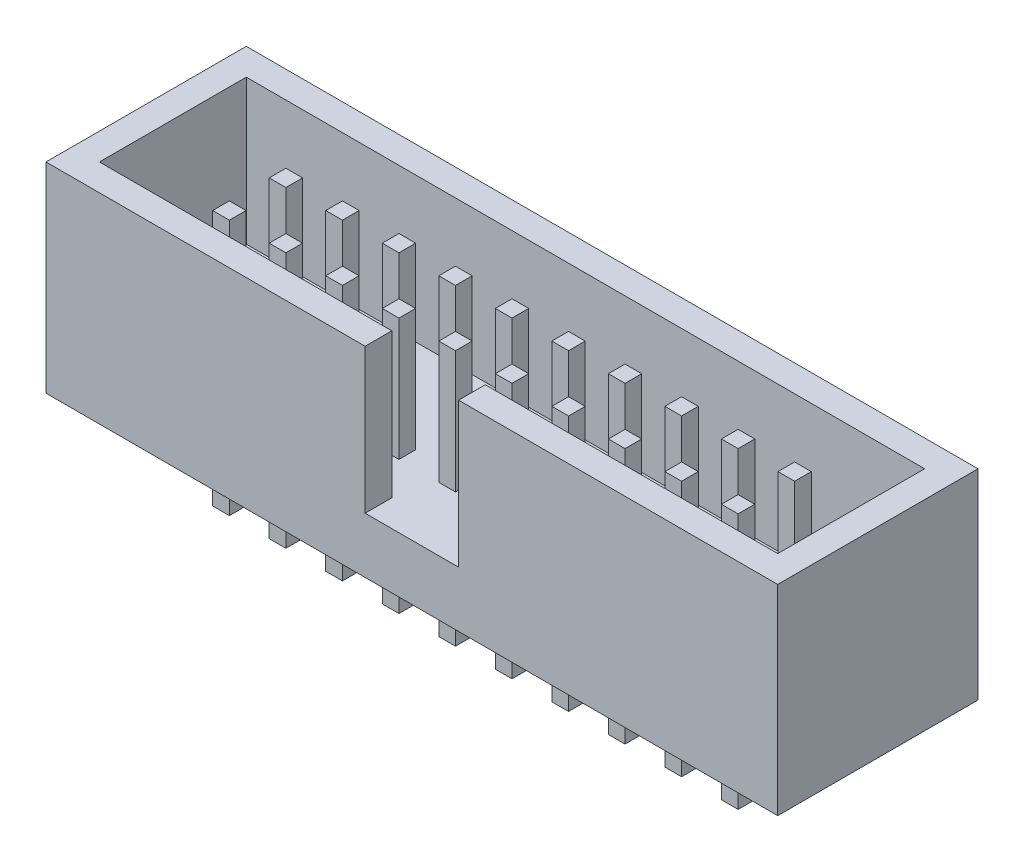
SolidWorks part; units mm, degrees
ref_plane "前视基准面" through (0, 0, 0) normal (0, 0, 1) x (1, 0, 0)
ref_plane "上视基准面" through (0, 0, 0) normal (0, 1, 0) x (1, 0, 0)
ref_plane "右视基准面" through (0, 0, 0) normal (1, 0, 0) x (0, 0, -1)
sketch "草图1" plane through (0, 0, 0) normal (0, 1, 0) x (1, 0, 0)
  line L0 (0, 85.0964) -> (0, -118.2031) construction
  line L1 (-16.44, 4.5) -> (16.44, 4.5)
  line L2 (-16.44, 4.5) -> (-16.44, -4.5)
  line L3 (-16.44, -4.5) -> (16.44, -4.5)
  line L4 (16.44, 4.5) -> (16.44, -4.5)
  line L5 (-200.5452, 0) -> (261.2352, 0) construction
  dimension "D1" = 9
  dimension "D2" = 32.88
extrude "拉伸1" add sketch "草图1" along normal blind 9
sketch "草图2" plane through (0, 9, 0) normal (0, 1, 0) x (-1, 0, 0)
  line L8 (-15.24, 3.3) -> (-15.24, -3.3)
  line L9 (15.24, 3.3) -> (-15.24, 3.3)
  line L10 (15.24, -3.3) -> (15.24, 3.3)
  line L11 (-15.24, -3.3) -> (15.24, -3.3)
  line L12 (-15.24, 3.3) -> (-15.24, -3.3)
  line L13 (15.24, 3.3) -> (-15.24, 3.3)
  line L14 (15.24, -3.3) -> (15.24, 3.3)
  line L15 (-15.24, -3.3) -> (15.24, -3.3)
  dimension "D1" = 1.2
extrude "切除-拉伸1" cut sketch "草图2" against normal blind 6.5
sketch "草图3" plane through (0, 0, 4.5) normal (0, 0, 1) x (1, 0, 0)
  line L0 (-16.44, 9) -> (16.44, 9) construction
  line L1 (-2.1, 9) -> (2.1, 9)
  line L2 (-2.1, 9) -> (-2.1, 2.5)
  line L3 (-2.1, 2.5) -> (2.1, 2.5)
  line L4 (2.1, 9) -> (2.1, 2.5)
  line L5 (-15.24, 2.5) -> (15.24, 2.5) construction
  line L6 (0, 9.4226) -> (0, -4.0288) construction
  dimension "D1" = 4.2
extrude "切除-拉伸2" cut sketch "草图3" against normal blind 6.5
sketch "草图5" plane through (0, 0, 0) normal (0, -1, 0) x (1, 0, 0)
  line L0 (0, 6.0683) -> (0, -6.9786) construction
  line L1 (-14.7999, 0) -> (15.2382, 0) construction
  line L2 (-1.27, 2.5244) -> (-1.27, -0.4442) construction
  line L3 (-1.645, 0.895) -> (-0.895, 0.895)
  line L4 (-1.645, 0.895) -> (-1.645, 1.645)
  line L5 (-1.645, 1.645) -> (-0.895, 1.645)
  line L6 (-0.895, 0.895) -> (-0.895, 1.645)
  line L7 (-2.3518, 1.27) -> (0.5396, 1.27) construction
  line L8 (0.895, 0.895) -> (1.645, 0.895)
  line L9 (0.895, 0.895) -> (0.895, 1.645)
  line L10 (0.895, 1.645) -> (1.645, 1.645)
  line L11 (1.645, 0.895) -> (1.645, 1.645)
  line L12 (3.435, 0.895) -> (4.185, 0.895)
  line L13 (3.435, 0.895) -> (3.435, 1.645)
  line L14 (3.435, 1.645) -> (4.185, 1.645)
  line L15 (4.185, 0.895) -> (4.185, 1.645)
  line L16 (5.975, 0.895) -> (6.725, 0.895)
  line L17 (5.975, 0.895) -> (5.975, 1.645)
  line L18 (5.975, 1.645) -> (6.725, 1.645)
  line L19 (6.725, 0.895) -> (6.725, 1.645)
  line L20 (8.515, 0.895) -> (9.265, 0.895)
  line L21 (8.515, 0.895) -> (8.515, 1.645)
  line L22 (8.515, 1.645) -> (9.265, 1.645)
  line L23 (9.265, 0.895) -> (9.265, 1.645)
  line L24 (11.055, 0.895) -> (11.805, 0.895)
  line L25 (11.055, 0.895) -> (11.055, 1.645)
  line L26 (11.055, 1.645) -> (11.805, 1.645)
  line L27 (11.805, 0.895) -> (11.805, 1.645)
  line L32 (0.895, -1.645) -> (1.645, -1.645)
  line L33 (0.895, -1.645) -> (0.895, -0.895)
  line L34 (0.895, -0.895) -> (1.645, -0.895)
  line L35 (1.645, -1.645) -> (1.645, -0.895)
  line L36 (3.435, -1.645) -> (4.185, -1.645)
  line L37 (3.435, -1.645) -> (3.435, -0.895)
  line L38 (3.435, -0.895) -> (4.185, -0.895)
  line L39 (4.185, -1.645) -> (4.185, -0.895)
  line L40 (5.975, -1.645) -> (6.725, -1.645)
  line L41 (5.975, -1.645) -> (5.975, -0.895)
  line L42 (5.975, -0.895) -> (6.725, -0.895)
  line L43 (6.725, -1.645) -> (6.725, -0.895)
  line L44 (8.515, -1.645) -> (9.265, -1.645)
  line L45 (8.515, -1.645) -> (8.515, -0.895)
  line L46 (8.515, -0.895) -> (9.265, -0.895)
  line L47 (9.265, -1.645) -> (9.265, -0.895)
  line L48 (11.055, -1.645) -> (11.805, -1.645)
  line L49 (11.055, -1.645) -> (11.055, -0.895)
  line L50 (11.055, -0.895) -> (11.805, -0.895)
  line L51 (11.805, -1.645) -> (11.805, -0.895)
  line L54 (-4.185, 0.895) -> (-3.435, 0.895)
  line L55 (-4.185, 0.895) -> (-4.185, 1.645)
  line L56 (-4.185, 1.645) -> (-3.435, 1.645)
  line L57 (-3.435, 0.895) -> (-3.435, 1.645)
  line L58 (-6.725, 0.895) -> (-5.975, 0.895)
  line L59 (-6.725, 0.895) -> (-6.725, 1.645)
  line L60 (-6.725, 1.645) -> (-5.975, 1.645)
  line L61 (-5.975, 0.895) -> (-5.975, 1.645)
  line L62 (-9.265, 0.895) -> (-8.515, 0.895)
  line L63 (-9.265, 0.895) -> (-9.265, 1.645)
  line L64 (-9.265, 1.645) -> (-8.515, 1.645)
  line L65 (-8.515, 0.895) -> (-8.515, 1.645)
  line L66 (-11.805, 0.895) -> (-11.055, 0.895)
  line L67 (-11.805, 0.895) -> (-11.805, 1.645)
  line L68 (-11.805, 1.645) -> (-11.055, 1.645)
  line L69 (-11.055, 0.895) -> (-11.055, 1.645)
  line L70 (-1.645, -1.645) -> (-0.895, -1.645)
  line L71 (-1.645, -1.645) -> (-1.645, -0.895)
  line L72 (-1.645, -0.895) -> (-0.895, -0.895)
  line L73 (-0.895, -1.645) -> (-0.895, -0.895)
  line L74 (-4.185, -1.645) -> (-3.435, -1.645)
  line L75 (-4.185, -1.645) -> (-4.185, -0.895)
  line L76 (-4.185, -0.895) -> (-3.435, -0.895)
  line L77 (-3.435, -1.645) -> (-3.435, -0.895)
  line L78 (-6.725, -1.645) -> (-5.975, -1.645)
  line L79 (-6.725, -1.645) -> (-6.725, -0.895)
  line L80 (-6.725, -0.895) -> (-5.975, -0.895)
  line L81 (-5.975, -1.645) -> (-5.975, -0.895)
  line L82 (-9.265, -1.645) -> (-8.515, -1.645)
  line L83 (-9.265, -1.645) -> (-9.265, -0.895)
  line L84 (-9.265, -0.895) -> (-8.515, -0.895)
  line L85 (-8.515, -1.645) -> (-8.515, -0.895)
  line L86 (-11.805, -1.645) -> (-11.055, -1.645)
  line L87 (-11.805, -1.645) -> (-11.805, -0.895)
  line L88 (-11.805, -0.895) -> (-11.055, -0.895)
  line L89 (-11.055, -1.645) -> (-11.055, -0.895)
  line L92 (-1.645, -1.645) -> (-0.895, -1.645) [skipped]
  line L93 (-0.895, -1.645) -> (-0.895, -0.895) [skipped]
  line L94 (-1.645, -0.895) -> (-0.895, -0.895) [skipped]
  line L95 (-1.645, -1.645) -> (-1.645, -0.895) [skipped]
  dimension "D1" = 0.75
  dimension "D2" = 0.75
  dimension "D3" = 1.27
  dimension "D4" = 1.27
extrude "拉伸2" add sketch "草图5" along normal blind 3.5 and the other way offset from surface (8 mm away) 1 other way up to face at (0, 9, 1.3)
